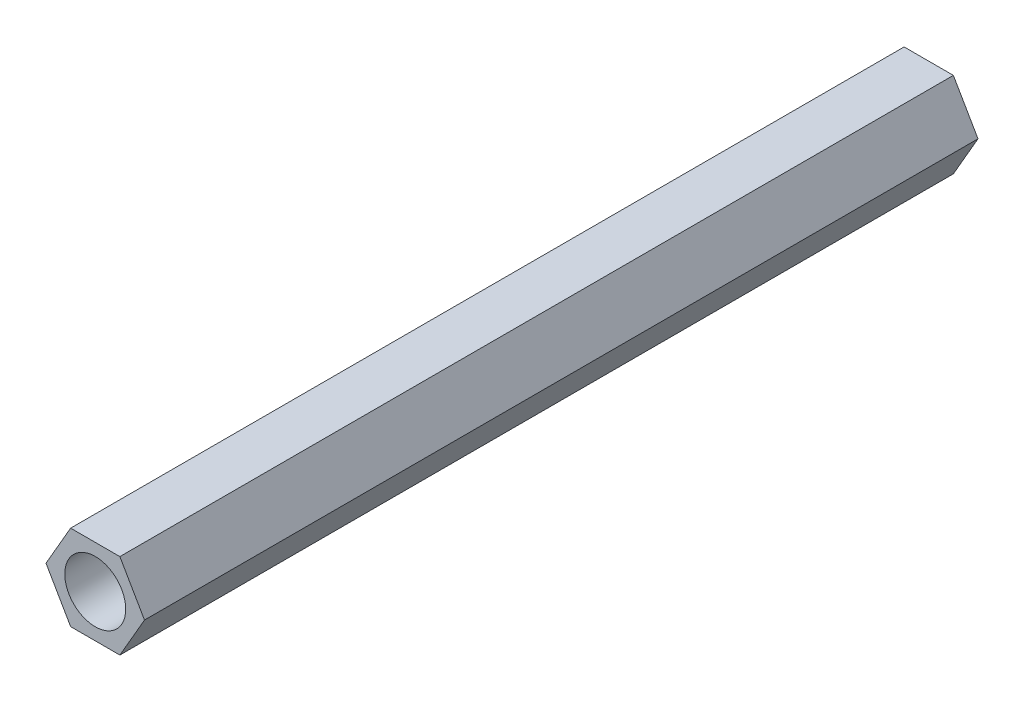
SolidWorks part; units mm, degrees
ref_plane "Front Plane" through (0, 0, 0) normal (0, 0, 1) x (1, 0, 0)
ref_plane "Top Plane" through (0, 0, 0) normal (0, 1, 0) x (1, 0, 0)
ref_plane "Right Plane" through (0, 0, 0) normal (1, 0, 0) x (0, 0, -1)
sketch "Sketch1" plane through (0, 0, 0) normal (0, 0, 1) x (1, 0, 0)
  line L1 (-4.0415, 0) -> (-2.0207, -3.5)
  line L2 (-2.0207, -3.5) -> (2.0207, -3.5)
  line L3 (2.0207, -3.5) -> (4.0415, 0)
  line L4 (4.0415, 0) -> (2.0207, 3.5)
  line L5 (2.0207, 3.5) -> (-2.0207, 3.5)
  line L6 (-2.0207, 3.5) -> (-4.0415, 0)
  circle A0 centre (0, 0) radius 2.5
  circle A1 centre (0, 0) radius 3.5 construction
  dimension "D1" = 5
  dimension "D2" = 7
extrude "Boss-Extrude1" add sketch "Sketch1" along normal mid plane 68.4
